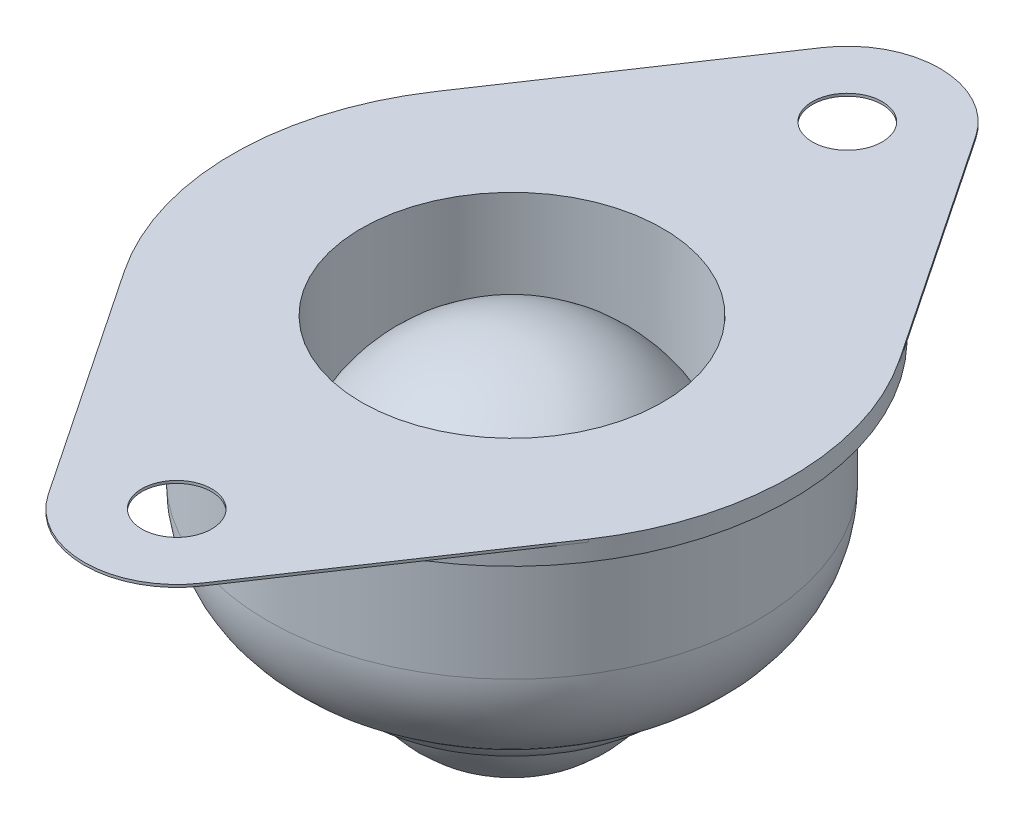
SolidWorks part; units mm, degrees
ref_plane "Front Plane" through (0, 0, 0) normal (0, 0, 1) x (1, 0, 0)
ref_plane "Top Plane" through (0, 0, 0) normal (0, 1, 0) x (1, 0, 0)
ref_plane "Right Plane" through (0, 0, 0) normal (1, 0, 0) x (0, 0, -1)
sketch "Sketch1" plane through (0, 0, 0) normal (0, 0, 1) x (1, 0, 0)
  line L0 (0, 0) -> (0, 32.2637) construction
  line L1 (16, 21.11) -> (16, 20.1237)
  line L2 (14, 19.11) -> (14, 13.11)
  line L3 (0, 0) -> (21.5489, 0) construction
  line L6 (16, 21.11) -> (8.6263, 21.11)
  line L7 (8.6263, 21.11) -> (8.6263, 14.305)
  line L8 (0, 20.2219) -> (6.0262, 20.2219) construction
  line L9 (0, 20.2219) -> (0, 0)
  arc A0 (14, 19.11) -> (16, 20.1237) centre (15.749, 18.1391) cw
  arc A1 (14, 13.11) -> (9.4986, 6.7456) centre (7.2501, 13.11) cw
  arc A2 (9.4986, 6.7456) -> (7.0965, 5.073) centre (7.3015, 7.3398) cw
  arc A3 (7.0965, 5.073) -> (0, 0) centre (0, 7.5) cw
  arc A4 (8.6263, 14.305) -> (0, 20.2219) centre (0, 10.9753) ccw
  point P3 (16, 21.11)
  dimension "D5" = 7.5
  dimension "D1" = 32
  dimension "D2" = 21.11
  dimension "D3" = 28
  dimension "D4" = 2
  dimension "D6" = 6
revolve "Revolve1" add sketch "Sketch1" angle 360 about L9
sketch "Sketch2" plane through (0, 21.11, 0) normal (0, 1, 0) x (1, 0, 0)
  line L0 (0, 0) -> (16, 0) construction
  line L1 (-4.4007, -22.1536) -> (-13.2851, -8.9167)
  line L2 (4.4007, -22.1536) -> (13.2851, -8.9167)
  line L3 (4.4007, 22.1536) -> (13.2851, 8.9167)
  line L4 (-4.4007, 22.1536) -> (-13.2851, 8.9167)
  arc A0 (4.4007, 22.1536) -> (-4.4007, 22.1536) centre (0, 19.2) ccw
  circle A1 centre (0, 0) radius 8.6263 construction
  arc A2 (4.4007, -22.1536) -> (-4.4007, -22.1536) centre (0, -19.2) cw
  circle A3 centre (0, 0) radius 16 construction
  arc A4 (-13.2851, 8.9167) -> (-13.2851, -8.9167) centre (0, 0) ccw
  arc A7 (13.2851, -8.9167) -> (13.2851, 8.9167) centre (0, 0) ccw
  circle A8 centre (0, 0) radius 8.6263
  circle A9 centre (0, -19.2) radius 2
  circle A10 centre (0, 19.2) radius 2
  point P0 (0, 24.5)
  point P9 (0, -24.5)
  point P20 (0, 17.2)
  point P22 (0, -17.2)
  dimension "D4" = 34.4
  dimension "D3" = 4
  dimension "D1" = 49
extrude "Boss-Extrude2" add sketch "Sketch2" along normal blind 0.15
